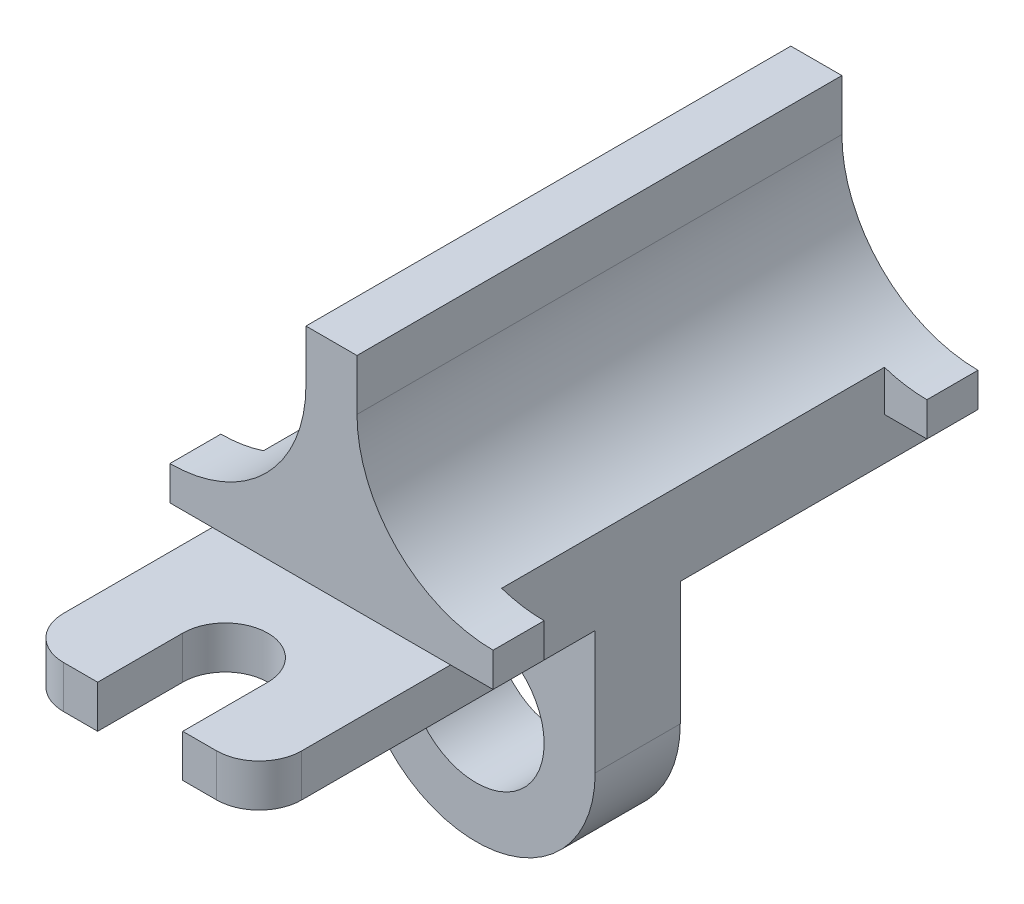
SolidWorks part; units mm, degrees
ref_plane "Front Plane" through (0, 0, 0) normal (0, 0, 1) x (1, 0, 0)
ref_plane "Top Plane" through (0, 0, 0) normal (0, 1, 0) x (1, 0, 0)
ref_plane "Right Plane" through (0, 0, 0) normal (1, 0, 0) x (0, 0, -1)
sketch "Sketch1" plane through (0, 0, 0) normal (0, 0, 1) x (1, 0, 0)
  line L0 (-37.3942, 0) -> (0, 0) construction
  line L16 (0, 0) -> (0, 29)
  line L17 (0, 29) -> (56, 29)
  line L18 (56, 29) -> (56, 0)
  arc A1 (56, 0) -> (0, 0) centre (28, 0) cw
  circle A2 centre (28, 0) radius 16
  point P12 (0, 0)
  dimension "D4" = 32
  dimension "D1" = 28
  dimension "D2" = 29
sketch "Sketch5" plane through (0, 0, 0) normal (0, 0, 1) x (1, 0, 0)
  line L19 (22, 79) -> (22, 91)
  line L24 (66, 39) -> (-10, 39)
  line L25 (66, 39) -> (66, 47)
  line L26 (34, 91) -> (22, 91)
  line L27 (-10, 39) -> (-10, 47)
  line L28 (8.4802, 79) -> (34.2346, 79) construction
  line L29 (34, 79) -> (34, 91)
  line L30 (-10, 79) -> (-10, 47) construction
  line L31 (66, 47) -> (66, 79) construction
  arc A3 (22, 79) -> (-10, 47) centre (-10, 79) cw
  arc A4 (66, 47) -> (34, 79) centre (66, 79) cw
  point P12 (0, 0)
  dimension "D6" = 32
  dimension "D7" = 32
  dimension "D5" = 12
  dimension "D8" = 12
  dimension "D10" = 40
sketch "Sketch7" plane through (0, 0, 0) normal (0, 0, 1) x (1, 0, 0)
  line L1 (0, 39) -> (56, 39)
  line L2 (0, 39) -> (0, 29)
  line L3 (0, 29) -> (56, 29)
  line L4 (56, 39) -> (56, 29)
  line L5 (66, 39) -> (-10, 39) construction
  line L6 (0, -6.2315) -> (0, 62.0934) construction
  point P6 (0, 0)
extrude "Boss-Extrude3" add sketch "Sketch7" along normal blind 89 and the other way blind 70 contours L3 L4 L1 L2
extrude "Boss-Extrude4" add sketch "Sketch5" along normal blind 44 and the other way blind 70
extrude "Boss-Extrude5" add sketch "Sketch1" along normal blind 10 and the other way blind 10
sketch "Sketch9" plane through (0, 39, 0) normal (0, 1, 0) x (1, 0, 0)
  line L0 (38.0335, -69) -> (38.0335, -89)
  line L1 (0, -89) -> (56, -89) construction
  line L2 (38.0335, -89) -> (18.0335, -89)
  line L3 (18.0335, -89) -> (18.0335, -69)
  arc A0 (38.0335, -69) -> (18.0335, -69) centre (28.0335, -69) ccw
  dimension "D1" = 20
  dimension "D2" = 20
extrude "Cut-Extrude1" cut sketch "Sketch9" against normal up to next
fillet "Fillet1" radius 10 2 edges at (56, 34, 89) (0, 34, 89)
sketch "Sketch10" plane through (0, 39, 0) normal (0, -1, 0) x (1, 0, 0)
  line L0 (-10, -70) -> (-10, 44) construction
  line L1 (-10, 32) -> (0, 32)
  line L2 (-10, 32) -> (-10, -58)
  line L3 (-10, -58) -> (0, -58)
  line L4 (0, 32) -> (0, -58)
  line L5 (0, -70) -> (0, -10) construction
  line L6 (-10, 44) -> (0, 44) construction
  line L7 (56, -70) -> (56, 44) construction
  line L8 (56, 32) -> (66, 32)
  line L9 (56, 32) -> (56, -58)
  line L10 (56, -58) -> (66, -58)
  line L11 (66, 32) -> (66, -58)
  line L12 (66, -70) -> (66, 44) construction
  line L13 (56, 44) -> (66, 44) construction
  point P20 (0, 0)
  dimension "D1" = 90
  dimension "D2" = 12
  dimension "D3" = 90
  dimension "D4" = 12
extrude "Cut-Extrude3" cut sketch "Sketch10" against normal up to next
